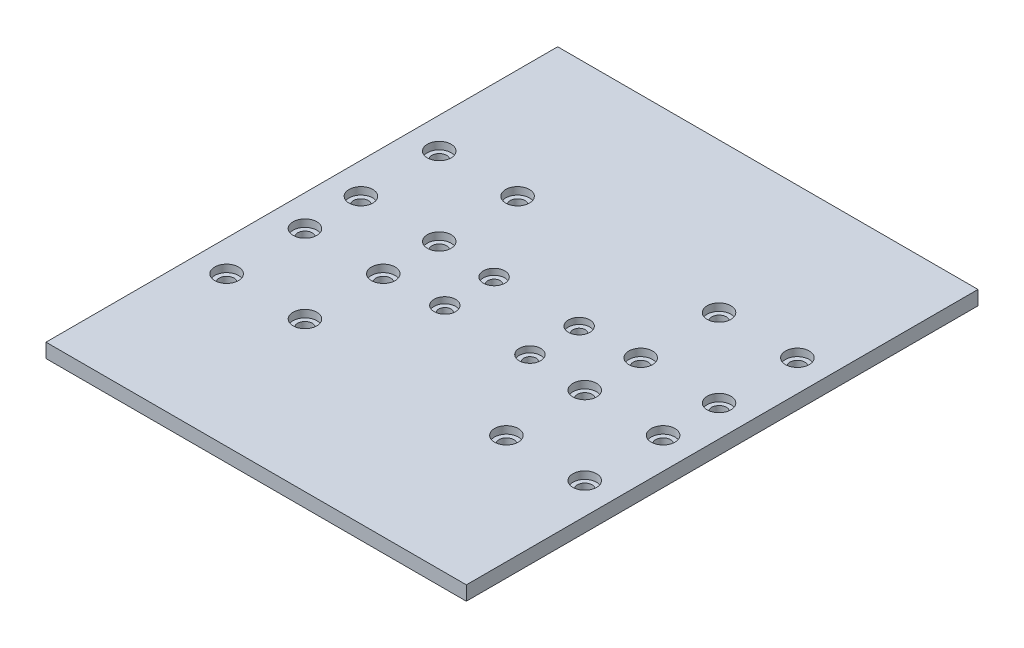
SolidWorks part; units mm, degrees
ref_plane "Front Plane" through (0, 0, 0) normal (0, 0, 1) x (1, 0, 0)
ref_plane "Top Plane" through (0, 0, 0) normal (0, 1, 0) x (1, 0, 0)
ref_plane "Right Plane" through (0, 0, 0) normal (1, 0, 0) x (0, 0, -1)
ref_plane "Plane1"
sketch "Sketch1" plane through (0, 0, 0) normal (0, 1, 0) x (-1, 0, 0)
  line L0 (93.9, 114.3) -> (-93.9, 114.3)
  line L1 (-93.9, 114.3) -> (-93.9, -114.3)
  line L2 (-93.9, -114.3) -> (93.9, -114.3)
  line L3 (93.9, -114.3) -> (93.9, 114.3)
  dimension "D1" = 187.8
  dimension "D2" = 228.6
extrude "Extrusion1" add sketch "Sketch1" along normal blind 6.35
hole_wizard "Hole4" positions "Sketch3" profile "Sketch2" legacy end condition through all
sketch "Sketch3" plane through (0, 6.35, 0) normal (0, 1, 0) x (1, 0, 0)
  point P1 (-80.0034, 12.5)
  point P2 (-80.0034, 47.5)
  point P3 (-80.0034, -12.5)
  point P4 (-80.0034, -47.5)
  point P5 (-45.0034, -12.5)
  point P6 (-45.0034, -47.5)
  point P7 (-45.0034, 12.5)
  point P8 (-45.0034, 47.5)
  point P9 (80.0034, 47.5)
  point P10 (80.0034, 12.5)
  point P11 (80.0034, -12.5)
  point P12 (80.0034, -47.5)
  point P13 (45.0034, -47.5)
  point P14 (45.0034, -12.5)
  point P15 (45.0034, 12.5)
  point P16 (45.0034, 47.5)
sketch "Sketch2" plane through (-80.0034, 6.35, -12.5) normal (1, 0, 0) x (0, 0, 1)
  line L0 (0, 0) -> (0, 6.35)
  line L1 (0, 6.35) -> (3.3, 6.35)
  line L2 (3.3, 6.35) -> (3.3, 0)
  line L3 (3.3, 0) -> (0, 0)
  line L4 (0, 110) -> (0, -10) construction
  dimension "Diameter" = 6.6
  dimension "Depth" = 6.35
hole_wizard "Hole5" positions "Sketch5" profile "Sketch4" legacy end condition through all
sketch "Sketch5" plane through (0, 6.35, 0) normal (0, 1, 0) x (1, 0, 0)
  point P1 (-19, 11)
  point P2 (19, 11)
  point P3 (-19, -11)
  point P4 (19, -11)
sketch "Sketch4" plane through (-19, 6.35, -11) normal (1, 0, 0) x (0, 0, 1)
  line L0 (0, 0) -> (0, 6.35)
  line L1 (0, 6.35) -> (2.75, 6.35)
  line L2 (2.75, 6.35) -> (2.75, 0)
  line L3 (2.75, 0) -> (0, 0)
  line L4 (0, 110) -> (0, -10) construction
  dimension "Diameter" = 5.5
  dimension "Depth" = 6.35
ref_plane "Plane2" through (-80.0034, 6.35, -47.5) normal (0, 1, 0) x (0, 0, -1)
hole_wizard "Hole6" positions "Sketch7" profile "Sketch6" legacy
sketch "Sketch7" plane through (-80.0034, 6.35, -47.5) normal (0, 1, 0) x (0, 0, -1)
  point P1 (0, 0)
  point P2 (0, -35)
  point P3 (-35, -35)
  point P4 (-35, 0)
  point P5 (-60, 0)
  point P6 (-60, -35)
  point P7 (-95, -35)
  point P8 (-95, 0)
  point P9 (-95, -160.0068)
  point P10 (-60, -160.0068)
  point P11 (0, -160.0068)
  point P12 (-35, -160.0068)
  point P13 (0, -125.0068)
  point P14 (-35, -125.0068)
  point P15 (-95, -125.0068)
  point P16 (-60, -125.0068)
sketch "Sketch6" plane through (-80.0034, 6.35, -47.5) normal (1, 0, 0) x (0, 0, 1)
  line L0 (0, 0) -> (0, 3.3)
  line L1 (0, 3.3) -> (5.3, 3.3)
  line L2 (5.3, 3.3) -> (5.3, 0)
  line L3 (5.3, 0) -> (0, 0)
  line L4 (0, 110) -> (0, -10) construction
  dimension "Diameter" = 10.6
  dimension "Depth" = 3.3
ref_plane "Plane3" through (-19, 6.35, -11) normal (0, 1, 0) x (0, 0, -1)
hole_wizard "Hole7" positions "Sketch9" profile "Sketch8" legacy
sketch "Sketch9" plane through (-19, 6.35, -11) normal (0, 1, 0) x (0, 0, -1)
  point P1 (0, 0)
  point P2 (0, -38)
  point P3 (-22, -38)
  point P4 (-22, 0)
sketch "Sketch8" plane through (-19, 6.35, -11) normal (1, 0, 0) x (0, 0, 1)
  line L0 (0, 0) -> (0, 2.75)
  line L1 (0, 2.75) -> (4.8, 2.75)
  line L2 (4.8, 2.75) -> (4.8, 0)
  line L3 (4.8, 0) -> (0, 0)
  line L4 (0, 110) -> (0, -10) construction
  dimension "Diameter" = 9.6
  dimension "Depth" = 2.75
